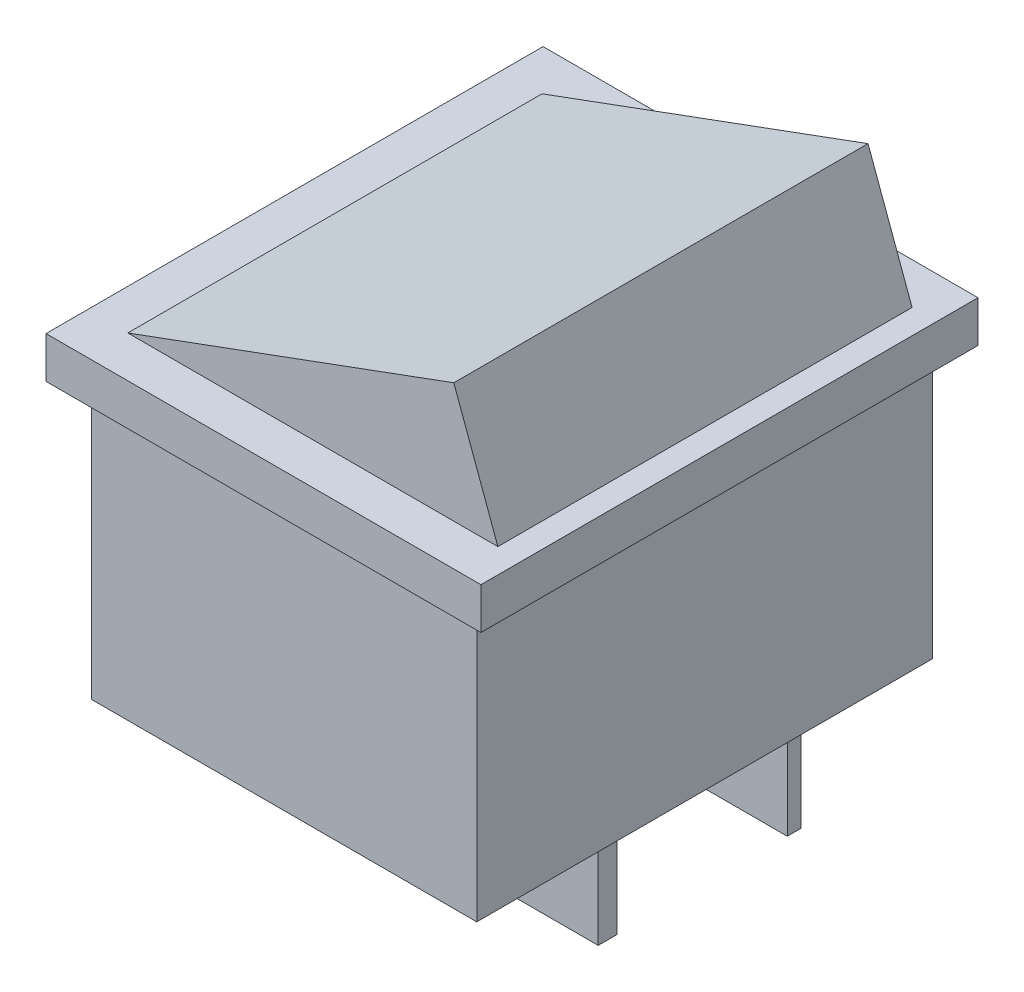
SolidWorks part; units mm, degrees
ref_plane "Front Plane" through (0, 0, 0) normal (0, 0, 1) x (1, 0, 0)
ref_plane "Top Plane" through (0, 0, 0) normal (0, 1, 0) x (1, 0, 0)
ref_plane "Right Plane" through (0, 0, 0) normal (1, 0, 0) x (0, 0, -1)
sketch "Sketch1" plane through (0, 0, 0) normal (0, 1, 0) x (1, 0, 0)
  line L1 (-10.5, -12) -> (10.5, -12)
  line L2 (-10.5, -12) -> (-10.5, 12)
  line L3 (-10.5, 12) -> (10.5, 12)
  line L4 (10.5, -12) -> (10.5, 12)
  line L5 (-10.5, -12) -> (10.5, 12) construction
  line L6 (-10.5, 12) -> (10.5, -12) construction
  point P0 (0, 0)
  dimension "D1" = 21
  dimension "D2" = 24
extrude "Boss-Extrude1" add sketch "Sketch1" along normal blind 2
sketch "Sketch2" plane through (0, 0, 0) normal (0, -1, 0) x (1, 0, 0)
  line L1 (-9.3, -11) -> (9.3, -11)
  line L2 (-9.3, -11) -> (-9.3, 11)
  line L3 (-9.3, 11) -> (9.3, 11)
  line L4 (9.3, -11) -> (9.3, 11)
  line L5 (-9.3, -11) -> (9.3, 11) construction
  line L6 (-9.3, 11) -> (9.3, -11) construction
  point P0 (0, 0)
  dimension "D1" = 18.6
  dimension "D2" = 22
extrude "Boss-Extrude2" add sketch "Sketch2" along normal blind 13.2
sketch "Sketch3" plane through (0, -13.2, 0) normal (0, -1, 0) x (1, 0, 0)
  line L1 (6.9149, 2.7533) -> (2.0294, 2.7533)
  line L2 (6.9149, 2.7533) -> (6.9149, 1.8567)
  line L3 (6.9149, 1.8567) -> (2.0294, 1.8567)
  line L4 (2.0294, 2.7533) -> (2.0294, 1.8567)
  line L5 (6.9149, 2.7533) -> (2.0294, 1.8567) construction
  line L6 (6.9149, 1.8567) -> (2.0294, 2.7533) construction
  line L7 (2.0294, -6.3762) -> (6.9149, -6.3762)
  line L8 (2.0294, -6.3762) -> (2.0294, -7.0377)
  line L9 (2.0294, -7.0377) -> (6.9149, -7.0377)
  line L10 (6.9149, -6.3762) -> (6.9149, -7.0377)
  line L11 (2.0294, -6.3762) -> (6.9149, -7.0377) construction
  line L12 (2.0294, -7.0377) -> (6.9149, -6.3762) construction
  line L13 (-7.5022, -6.3762) -> (-0.9865, -6.3762)
  line L14 (-7.5022, -6.3762) -> (-7.5022, -7.0377)
  line L15 (-7.5022, -7.0377) -> (-0.9865, -7.0377)
  line L16 (-0.9865, -6.3762) -> (-0.9865, -7.0377)
  line L17 (-7.5022, -6.3762) -> (-0.9865, -7.0377) construction
  line L18 (-7.5022, -7.0377) -> (-0.9865, -6.3762) construction
  line L19 (-7.5022, 2.7533) -> (-0.9865, 2.7533)
  line L20 (-7.5022, 2.7533) -> (-7.5022, 1.8567)
  line L21 (-7.5022, 1.8567) -> (-0.9865, 1.8567)
  line L22 (-0.9865, 2.7533) -> (-0.9865, 1.8567)
  line L23 (-7.5022, 2.7533) -> (-0.9865, 1.8567) construction
  line L24 (-7.5022, 1.8567) -> (-0.9865, 2.7533) construction
  point P0 (4.4722, 2.305)
  point P5 (4.4722, -6.7069)
  point P10 (-4.2444, -6.7069)
  point P15 (-4.2444, 2.305)
extrude "Boss-Extrude3" add sketch "Sketch3" along normal blind 6.3
sketch "Sketch4" plane through (0, 0, 0) normal (0, 0, 1) x (1, 0, 0)
  line L0 (-8.8034, 1.9071) -> (7.1894, 7.7875)
  line L1 (7.1894, 7.7875) -> (9.3806, 1.8281)
  line L2 (9.3806, 1.8281) -> (-8.8034, 1.9071)
  point P3 (-8.5218, 0.8725)
  point P4 (-8.8034, 1.9071)
  point P5 (9.3806, 1.8281)
extrude "Boss-Extrude4" add sketch "Sketch4" along normal mid plane 20
